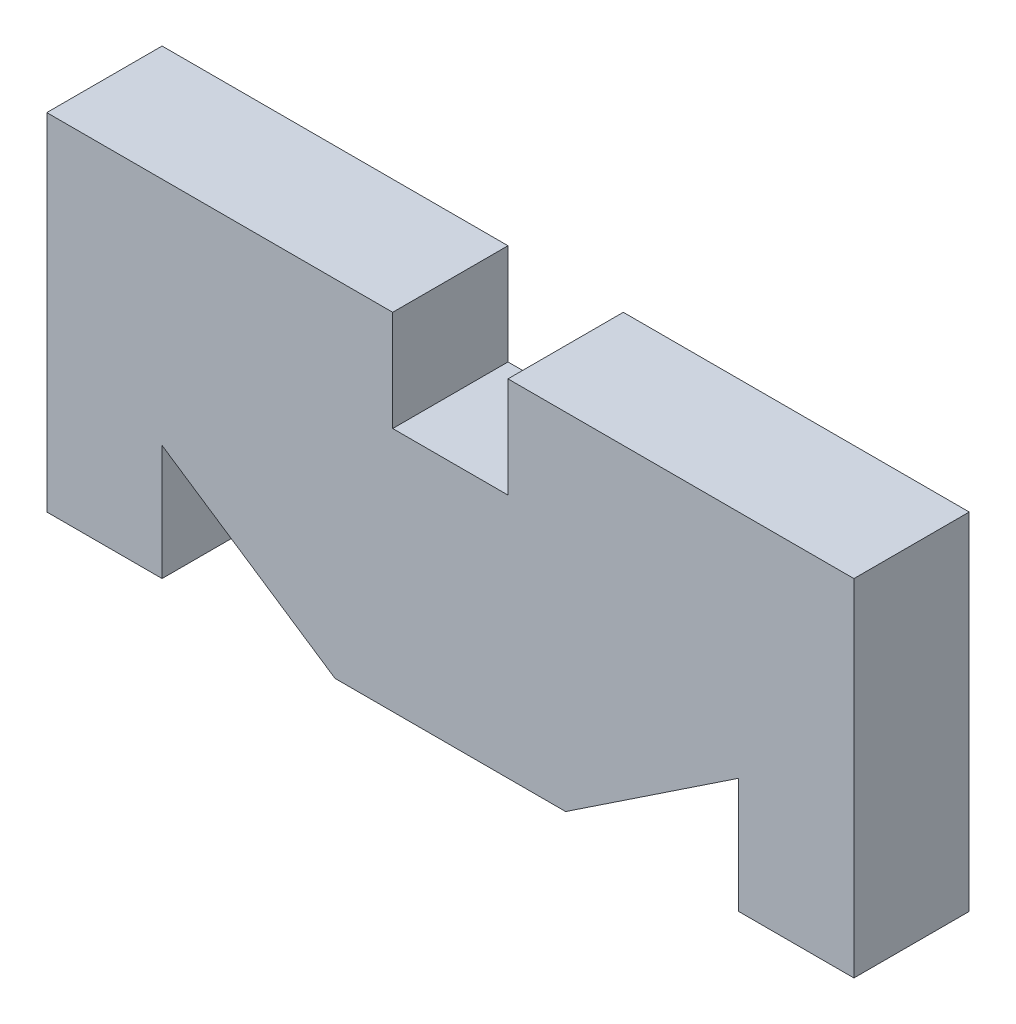
SolidWorks part; units mm, degrees
ref_plane "Ön Düzlem" through (0, 0, 0) normal (0, 0, 1) x (1, 0, 0)
ref_plane "Üst Düzlem" through (0, 0, 0) normal (0, 1, 0) x (1, 0, 0)
ref_plane "Sağ Düzlem" through (0, 0, 0) normal (1, 0, 0) x (0, 0, -1)
sketch "Çizim1" plane through (0, 0, 0) normal (0, 0, 1) x (1, 0, 0)
  line L0 (-25.0375, -11) -> (-25.0375, -1)
  line L1 (-35.0375, 19) -> (-5.0375, 19)
  line L2 (-35.0375, 19) -> (-35.0375, -11)
  line L3 (-35.0375, -11) -> (-25.0375, -11)
  line L4 (34.9625, 19) -> (34.9625, -11)
  line L5 (-25.0375, -1) -> (-10.0375, -11)
  line L6 (-10.0375, -11) -> (9.9625, -11)
  line L7 (24.9625, -11) -> (24.9625, -1)
  line L8 (24.9625, -1) -> (9.9625, -11)
  line L9 (24.9625, -11) -> (34.9625, -11)
  line L10 (-5.0375, 19) -> (-5.0375, 10.2698)
  line L11 (-5.0375, 10.2698) -> (4.9625, 10.2698)
  line L12 (4.9625, 10.2698) -> (4.9625, 19)
  line L13 (4.9625, 19) -> (34.9625, 19)
  dimension "D1" = 70
  dimension "D2" = 30
  dimension "D3" = 10
  dimension "D4" = 15
  dimension "D5" = 10
  dimension "D6" = 10
  dimension "D7" = 10
  dimension "D8" = 15
  dimension "D9" = 10
  dimension "D10" = 10
  dimension "D11" = 30
extrude "Yükseklik-Ekstrüzyon1" add sketch "Çizim1" along normal blind 10
